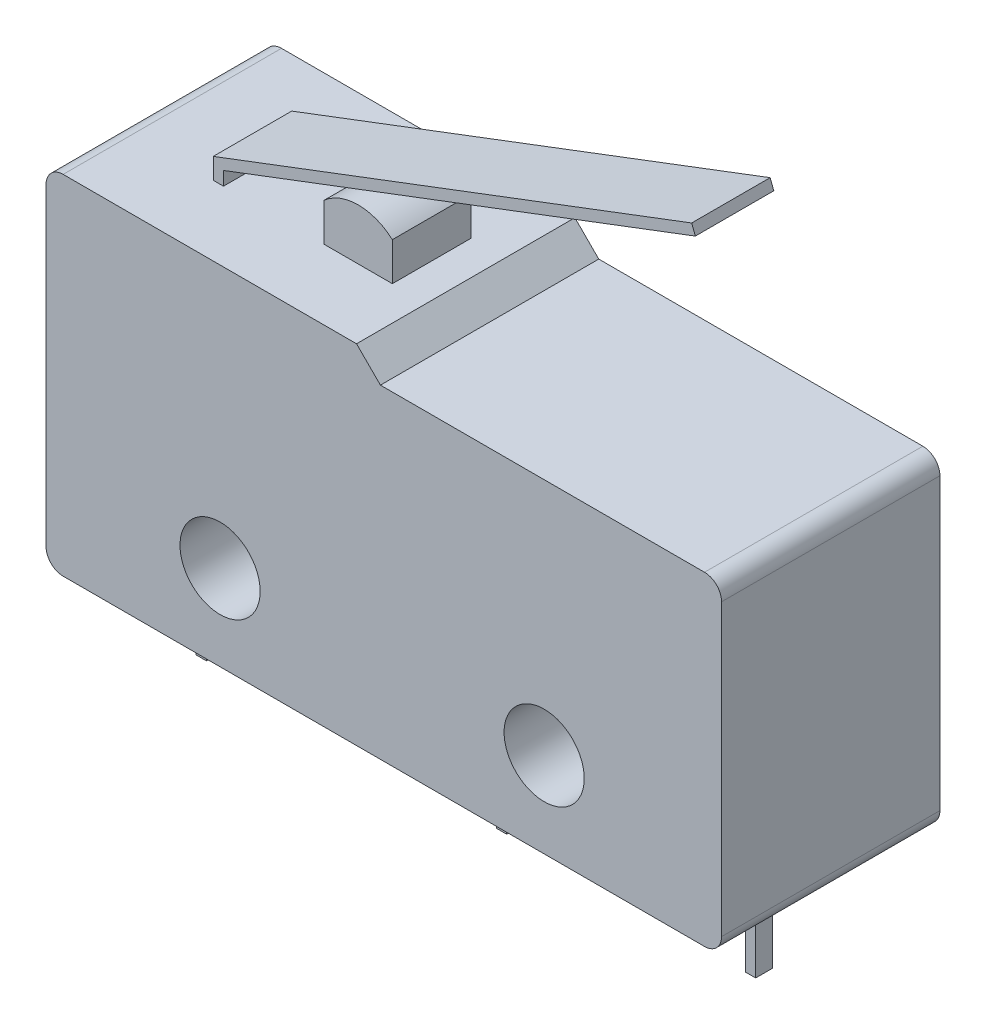
SolidWorks part; units mm, degrees
ref_plane "前视基准面" through (0, 0, 0) normal (0, 0, 1) x (1, 0, 0)
ref_plane "上视基准面" through (0, 0, 0) normal (0, 1, 0) x (1, 0, 0)
ref_plane "右视基准面" through (0, 0, 0) normal (1, 0, 0) x (0, 0, -1)
other "Configuration Table"
sketch "草图1" plane through (0, 0, 0) normal (0, 0, 1) x (1, 0, 0)
  line L0 (0, 0) -> (2030.8321, 0) construction
  line L1 (0, 0) -> (0, -2030.8321) construction
  line L2 (0.5, 0) -> (9.1, 0)
  line L3 (9.1, 0) -> (9.8, -0.7)
  line L4 (9.8, -0.7) -> (19.3, -0.7)
  line L5 (19.8, -1.2) -> (19.8, -9.7)
  line L6 (19.3, -10.2) -> (0.5, -10.2)
  line L7 (0, -9.7) -> (0, -0.5)
  line L8 (-1.9206, -7.7) -> (49998.0794, -7.7) construction
  line L9 (14.6, -7.7) -> (14.6, 49992.3) construction
  line L10 (7.1, 3.152) -> (7.1, -49996.848) construction
  circle A0 centre (5.1, -7.7) radius 1.175
  circle A1 centre (14.6, -7.7) radius 1.175
  arc A2 (0.5, 0) -> (0, -0.5) centre (0.5, -0.5) ccw
  arc A3 (0.5, -10.2) -> (0, -9.7) centre (0.5, -9.7) cw
  arc A4 (19.8, -9.7) -> (19.3, -10.2) centre (19.3, -9.7) cw
  arc A5 (19.3, -0.7) -> (19.8, -1.2) centre (19.3, -1.2) cw
  point P23 (0, 0)
  point P26 (0, -10.2)
  point P29 (19.8, -10.2)
  point P32 (19.8, -0.7)
  dimension "D5" = 2.35
  dimension "D6" = 2.35
  dimension "D12" = 0.5
  dimension "D13" = 0.5
  dimension "D1" = 10.2
  dimension "D2" = 9.5
  dimension "D3" = 19.8
  dimension "D4" = 2.5
  dimension "D7" = 5.1
  dimension "D8" = 9.5
  dimension "D9" = 135
  dimension "D10" = 7.5
  dimension "D11" = 2
extrude "凸台-拉伸1" add sketch "草图1" along normal mid plane 6.4
sketch "草图2" plane through (0, 0, 0) normal (0, 0, 1) x (1, 0, 0)
  line L0 (14.6, -7.7) -> (14.6, -50007.7) construction
  line L1 (7.1, 1.859) -> (7.1, -49998.141) construction
  line L2 (6.1, 1.118) -> (6.1, 0)
  line L3 (9.1, 0) -> (0.5, 0) construction
  line L4 (6.1, 0) -> (8.1, 0)
  line L5 (8.1, 0) -> (8.1, 1.118)
  line L6 (13.9, -7.7) -> (50013.9, -7.7) construction
  line L7 (16.8703, 5.9) -> (-49983.1297, 5.9) construction
  arc A1 (6.1, 1.118) -> (8.1, 1.118) centre (7.1, 0) cw
  point P13 (7.1, 0)
  point P21 (0, 0)
  point P22 (3.1652, 0.2122)
  point P23 (13.7744, 5.4344)
  point P24 (15.4145, 3.6858)
  point P25 (3.5968, 0.9374)
  point P26 (18.0849, 5.9)
  point P27 (3.6803, 0.4139)
  point P28 (2.9735, 0.618)
  point P29 (2.3734, 0)
  point P30 (4.1253, 1.0159)
  point P31 (4.2715, 1.33)
  point P32 (3.3662, 0.6756)
  point P33 (3.232, 1.118)
  point P34 (2.9571, 0.9052)
  dimension "D3" = 1.5
  dimension "D1" = 7.5
  dimension "D2" = 2
  dimension "D4" = 13.6
  dimension "D6" = 0
extrude "凸台-拉伸2" add sketch "草图2" along normal mid plane 2.3
sketch "草图4" plane through (0, 0, 0) normal (0, 0, 1) x (1, 0, 0)
  line L0 (3, 1.9993) -> (3, -49998.0007) construction
  line L1 (13.9, -7.7) -> (50013.9, -7.7) construction
  line L2 (6.1334, 5.9) -> (50006.1334, 5.9) construction
  line L3 (0, -0.5) -> (0, -9.7) construction
  line L8 (2.85, 0) -> (3.15, 0)
  line L9 (9.1, 0) -> (0.5, 0) construction
  line L10 (3.15, 0) -> (3.15, 0.4)
  line L11 (3.15, 0.4) -> (16.9806, 5.6485)
  line L12 (16.9806, 5.6485) -> (16.8742, 5.9289)
  line L13 (16.8742, 5.9289) -> (2.85, 0.607)
  line L14 (2.85, 0.607) -> (2.85, 0)
  point P13 (2.85, 1.1889)
  point P18 (0, 0)
  point P19 (3.15, 0.9584)
  point P20 (16.8047, 6.2316)
  point P24 (17.108, 5.6175)
  dimension "D1" = 13.6
  dimension "D2" = 3
  dimension "D3" = 0.3
  dimension "D4" = 0.15
  dimension "D5" = 0.3
  dimension "D6" = 15
  dimension "D7" = 0.4
extrude "凸台-拉伸10" add sketch "草图4" along normal mid plane 2.3
sketch "草图5" plane through (0, 0, 0) normal (0, 0, 1) x (1, 0, 0)
  line L0 (1.6, -4.2233) -> (1.6, -50004.2233) construction
  line L1 (10.4, -3.6921) -> (10.4, -50003.6921) construction
  line L2 (17.7, -3.2426) -> (17.7, -50003.2426) construction
  line L3 (0, -0.5) -> (0, -9.7) construction
  line L4 (0.5, -10.2) -> (19.3, -10.2) construction
  line L5 (1.45, -13.2) -> (1.75, -13.2)
  line L6 (1.45, -13.2) -> (1.45, -10.2)
  line L7 (1.45, -10.2) -> (1.75, -10.2)
  line L8 (1.75, -13.2) -> (1.75, -10.2)
  line L9 (1.45, -13.2) -> (1.75, -10.2) construction
  line L10 (1.45, -10.2) -> (1.75, -13.2) construction
  line L12 (10.25, -13.2) -> (10.55, -13.2)
  line L13 (10.25, -13.2) -> (10.25, -10.2)
  line L14 (10.25, -10.2) -> (10.55, -10.2)
  line L15 (10.55, -13.2) -> (10.55, -10.2)
  line L16 (10.25, -13.2) -> (10.55, -10.2) construction
  line L17 (10.25, -10.2) -> (10.55, -13.2) construction
  line L18 (17.55, -13.2) -> (17.85, -13.2)
  line L19 (17.55, -13.2) -> (17.55, -10.2)
  line L20 (17.55, -10.2) -> (17.85, -10.2)
  line L21 (17.85, -13.2) -> (17.85, -10.2)
  line L22 (17.55, -13.2) -> (17.85, -10.2) construction
  line L23 (17.55, -10.2) -> (17.85, -13.2) construction
  point P8 (1.6, -11.7)
  point P15 (10.4, -11.7)
  point P20 (17.7, -11.7)
  dimension "D1" = 1.6
  dimension "D2" = 8.8
  dimension "D3" = 7.3
  dimension "D4" = 0.3
  dimension "D5" = 0.3
  dimension "D6" = 0.3
  dimension "D7" = 3
extrude "凸台-拉伸12" add sketch "草图5" along normal mid plane 0.5
